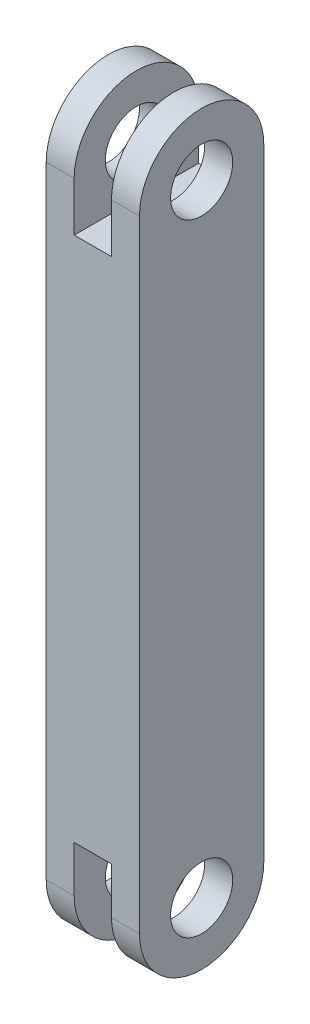
SolidWorks part; units mm, degrees
ref_plane "Front Plane" through (0, 0, 0) normal (1, 0, 0) x (0, 1, 0)
ref_plane "Top Plane" through (0, 0, 0) normal (0, 0, 1) x (0, 1, 0)
ref_plane "Right Plane" through (0, 0, 0) normal (0, 1, 0) x (-1, 0, 0)
sketch "Sketch1" plane through (0, 0, 0) normal (1, 0, 0) x (0, 1, 0)
  line L0 (0, 0) -> (127, 0) construction
  line L3 (0, 12.7) -> (127, 12.7)
  line L4 (0, -12.7) -> (127, -12.7)
  arc A2 (0, 12.7) -> (0, -12.7) centre (0, 0) ccw
  arc A3 (127, -12.7) -> (127, 12.7) centre (127, 0) ccw
  point P2 (63.5, 0)
  point P8 (-12.7, 0)
  dimension "D1" = 127
  dimension "D2" = 12.7
extrude "Boss-Extrude1" add sketch "Sketch1" along normal mid plane 19.05
sketch "Sketch3" plane through (0, 0, 12.7) normal (0, 0, 1) x (1, 0, 0)
  line L0 (-3.81, 116.9453) -> (-3.81, 147.0874)
  line L5 (0, 145.6336) -> (0, -25.6359) construction
  line L7 (-3.81, 147.0874) -> (3.81, 147.0874)
  line L8 (3.81, 147.0874) -> (3.81, 116.9453)
  line L10 (3.81, 116.9453) -> (-3.81, 116.9453)
  line L11 (-3.81, -20.6722) -> (-3.81, 9.4699)
  line L12 (-3.81, 9.4699) -> (3.81, 9.4699)
  line L13 (3.81, 9.4699) -> (3.81, -20.6722)
  line L14 (3.81, -20.6722) -> (-3.81, -20.6722)
  dimension "D1" = 3.81
  dimension "D2" = 3.81
  dimension "0.15" = 3.81
  dimension "D4" = 3.81
extrude "Cut-Extrude4" cut sketch "Sketch3" against normal through all both and the other way through all
sketch "Sketch5" plane through (9.525, 0, 0) normal (1, 0, 0) x (0, 1, 0)
  circle A0 centre (0, 0) radius 6.35
  circle A1 centre (127, 0) radius 6.35
  arc A2 (0, 12.7) -> (0, -12.7) centre (0, 0) ccw construction
  arc A4 (127, -12.7) -> (127, 12.7) centre (127, 0) ccw construction
  point P7 (-12.7, 0)
  point P11 (139.7, 0)
  dimension "D1" = 12.7
  dimension "D2" = 12.7
  dimension "D3" = 12.7
  dimension "D4" = 12.7
extrude "Cut-Extrude6" cut sketch "Sketch5" against normal through all both and the other way through all
